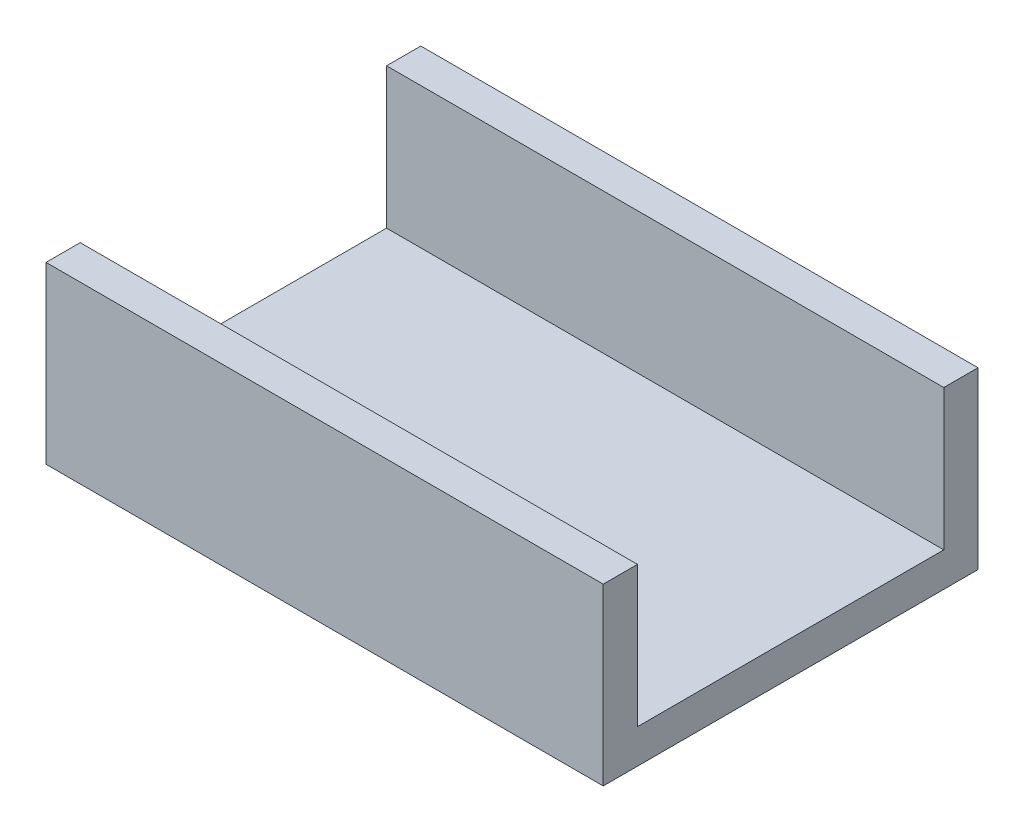
SolidWorks part; units mm, degrees
ref_plane "Front Plane" through (0, 0, 0) normal (0, 0, 1) x (1, 0, 0)
ref_plane "Top Plane" through (0, 0, 0) normal (0, 1, 0) x (1, 0, 0)
ref_plane "Right Plane" through (0, 0, 0) normal (1, 0, 0) x (0, 0, -1)
sketch "Sketch1" plane through (0, 0, 0) normal (0, 1, 0) x (1, 0, 0)
  line L1 (-81.4205, 54.7589) -> (81.4205, 54.7589)
  line L2 (-81.4205, 54.7589) -> (-81.4205, -54.7589)
  line L3 (-81.4205, -54.7589) -> (81.4205, -54.7589)
  line L4 (81.4205, 54.7589) -> (81.4205, -54.7589)
  line L5 (-81.4205, 54.7589) -> (81.4205, -54.7589) construction
  line L6 (-81.4205, -54.7589) -> (81.4205, 54.7589) construction
  point P0 (0, 0)
extrude "Boss-Extrude1" add sketch "Sketch1" along normal blind 10
sketch "Sketch3" plane through (0, 0, 54.7589) normal (0, 0, 1) x (1, 0, 0)
  line L0 (81.4205, 10) -> (81.4205, 0) construction
  line L1 (-81.4205, 10) -> (81.4205, 10)
  line L2 (-81.4205, 10) -> (-81.4205, 51.0859)
  line L3 (-81.4205, 51.0859) -> (81.4205, 51.0859)
  line L4 (81.4205, 10) -> (81.4205, 51.0859)
sketch "Sketch4" plane through (0, 10, 0) normal (0, 1, 0) x (1, 0, 0)
  line L0 (-96.2943, 0) -> (101.5928, 0) construction
extrude "Boss-Extrude2" add sketch "Sketch3" against normal blind 10
mirror "Mirror1" about plane through (0, 0, 0) normal (0, 0, 1) of "Boss-Extrude2"
